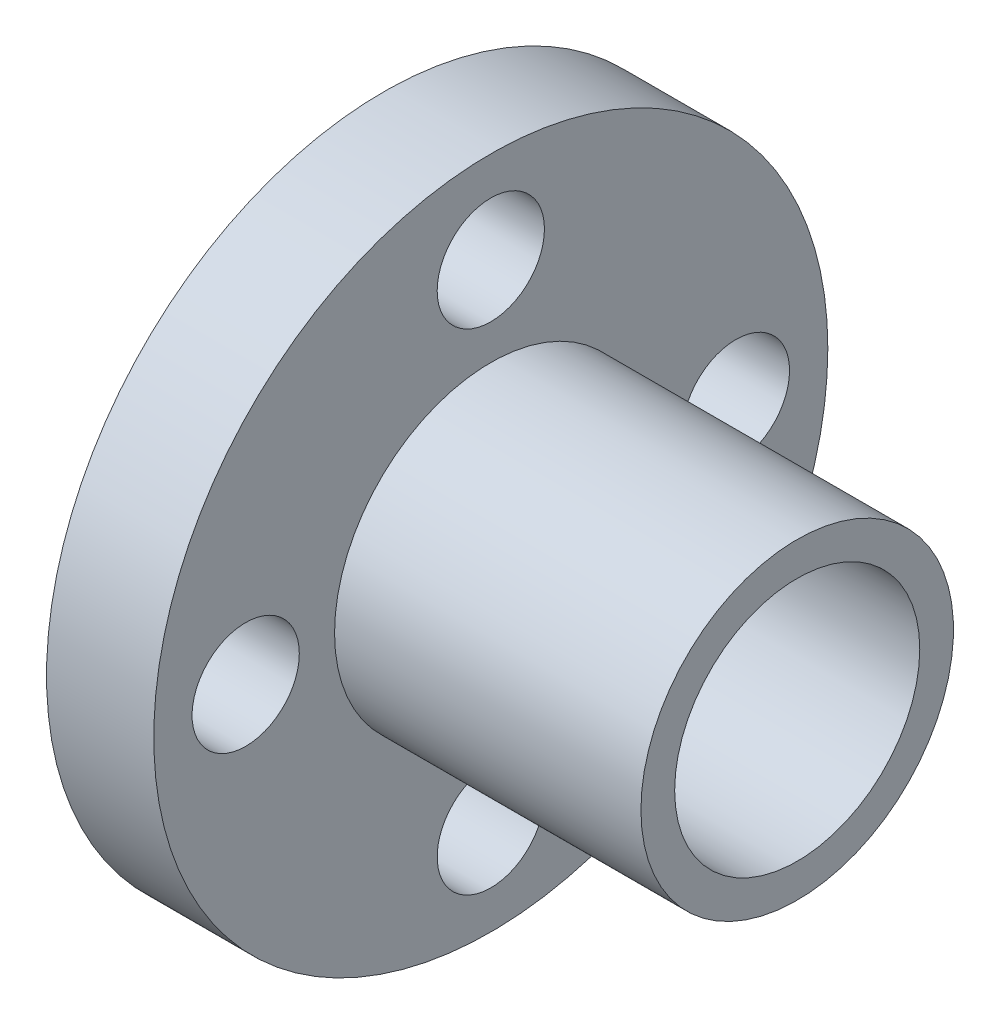
SolidWorks part; units mm, degrees
ref_plane "前视基准面" through (0, 0, 0) normal (0, 0, 1) x (1, 0, 0)
ref_plane "上视基准面" through (0, 0, 0) normal (0, 1, 0) x (1, 0, 0)
ref_plane "右视基准面" through (0, 0, 0) normal (1, 0, 0) x (0, 0, -1)
sketch "草图1" plane through (0, 0, 0) normal (1, 0, 0) x (0, 0, -1)
  circle A0 centre (0, 0) radius 11
extrude "凸台-拉伸1" add sketch "草图1" along normal blind 3.5 contours A0
sketch "草图2" plane through (0, 0, 0) normal (-1, 0, 0) x (0, 0, 1)
  circle A0 centre (0, 0) radius 5.1
extrude "凸台-拉伸2" add sketch "草图2" along normal blind 1.5 and the other way blind 13.5
sketch "草图3" plane through (-1.5, 0, 0) normal (-1, 0, 0) x (0, 0, 1)
  circle A0 centre (0, 0) radius 4
extrude "切除-拉伸1" cut sketch "草图3" against normal through all
sketch "草图4" plane through (0, 0, 0) normal (-1, 0, 0) x (0, 0, 1)
  line L0 (0, 0) -> (0, 8) construction
  circle A0 centre (0, 8) radius 1.75
extrude "切除-拉伸2" cut sketch "草图4" against normal through all
pattern_circular "阵列(圆周)1" count 4 over 360 about axis through (0, 0, 0) along (1, 0, 0) of "切除-拉伸2"
